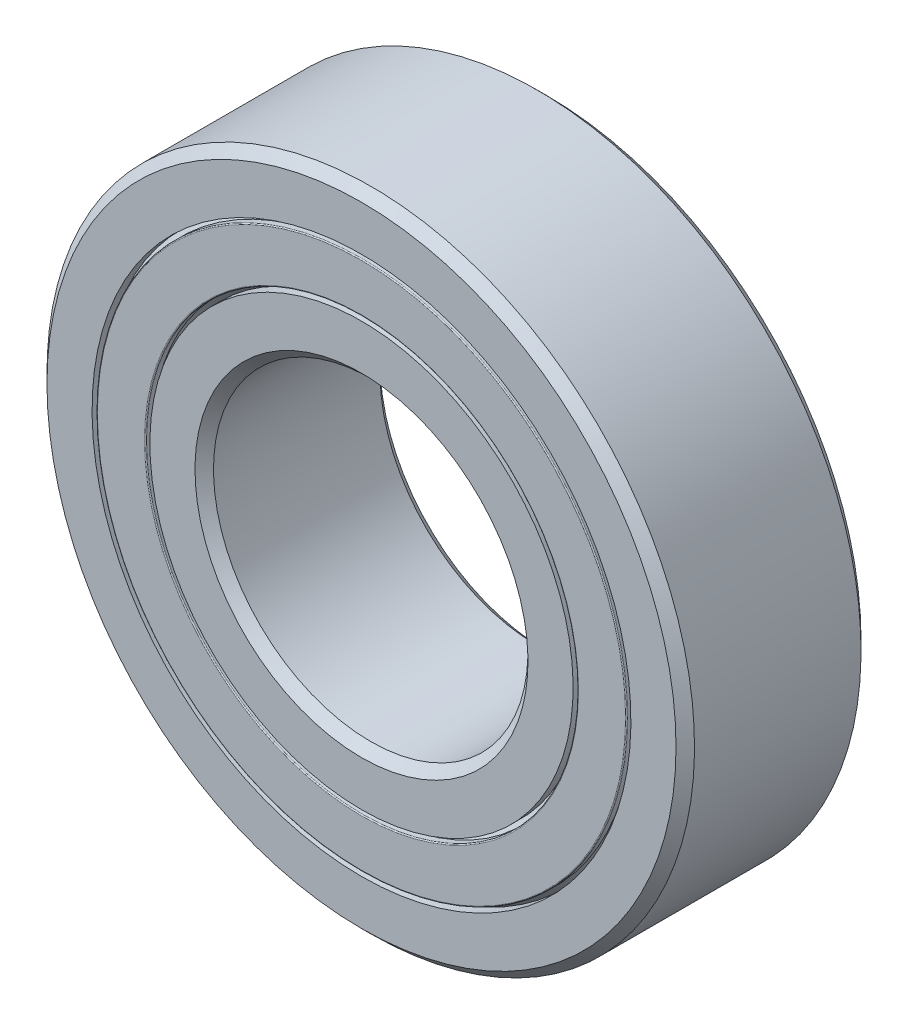
SolidWorks part; units mm, degrees
ref_plane "Front Plane" through (0, 0, 0) normal (0, 0, 1) x (1, 0, 0)
ref_plane "Top Plane" through (0, 0, 0) normal (0, 1, 0) x (1, 0, 0)
ref_plane "Right Plane" through (0, 0, 0) normal (1, 0, 0) x (0, 0, -1)
sketch "Sketch1" plane through (0, 0, 0) normal (0, 0, 1) x (1, 0, 0)
  line L0 (-17.5, 0) -> (17.5, 0) construction
  line L1 (-8.5, 0) -> (8.5, 0) construction
  circle A0 centre (0, 0) radius 8.5 construction
  circle A1 centre (0, 0) radius 17.5 construction
  point P3 (0, 0)
  point P6 (0, 0)
  point P7 (0, -8.5)
  point P11 (0, -17.5)
  point P12 (0, 8.5)
  point P13 (0, 17.5)
  dimension "OD" = 35
  dimension "ID" = 17
sketch "Sketch2" plane through (0, 0, 0) normal (1, 0, 0) x (0, 0, -1)
  line L0 (-5, 17.5) -> (5, 17.5) construction
  line L1 (0, 17.5) -> (0, -17.5) construction
  line L2 (4.5, 17.5) -> (-4.5, 17.5)
  line L3 (-4.5, 17.5) -> (-5, 17)
  line L4 (-5, 17) -> (-5, 14.5625)
  line L5 (-5, 14.5625) -> (-2.2222, 14.5625)
  line L6 (5, 14.5625) -> (2.2222, 14.5625)
  line L7 (5, 17) -> (5, 14.5625)
  line L8 (4.5, 17.5) -> (5, 17)
  line L9 (0, 17.5) -> (0, 13) construction
  line L10 (0, 13) -> (0, 8.5) construction
  line L11 (0, 17.5) -> (0, -17.5) construction
  line L12 (-5, 0) -> (5, 0) construction
  line L13 (5, 8.5) -> (-5, 8.5) construction
  line L14 (0, 15.7166) -> (0, 10.2834) construction
  line L15 (-5, -8.5) -> (5, -8.5) construction
  line L16 (-5, 8.5) -> (-5, -8.5) construction
  line L17 (5, 17.5) -> (5, -17.5) construction
  line L18 (-5, 14.5625) -> (-5, 14.4063) construction
  line L19 (-5, 14.4063) -> (-5, 14.25) construction
  line L20 (-5, 14.25) -> (-5, 14.0938) construction
  line L21 (-5, 14.0938) -> (-5, 13.9375) construction
  line L22 (-5, 13.9375) -> (-5, 13.7813) construction
  line L24 (-3.6111, 14.5625) -> (-3.6111, 13) construction
  arc A0 (-2.2222, 14.5625) -> (2.2222, 14.5625) centre (0, 13) cw
  circle A1 centre (0, 13) radius 2.7166 construction
  point P14 (0, 8.5)
  point P17 (0, 0)
  point P21 (0, 17.5)
  point P29 (0, 8.5)
  point P30 (0, -8.5)
  point P46 (-3.6111, 13.7813)
  dimension "Width" = 10
  dimension "D1" = 45
  dimension "D2" = 0.5
  dimension "D3" = 4.4444
  dimension "D4" = 1.5625
  dimension "For Shaft Diameter" = 17
  dimension "For Housing ID" = 35
sketch "Sketch3" plane through (0, 0, 0) normal (1, 0, 0) x (0, 0, -1)
  line L0 (4.5, 17.5) -> (5, 17) construction
  line L1 (5, 17) -> (5, 14.5625) construction
  line L2 (5, 14.5625) -> (2.2222, 14.5625) construction
  line L3 (-5, 14.5625) -> (-2.2222, 14.5625) construction
  line L4 (-5, 17) -> (-5, 14.5625) construction
  line L5 (-4.5, 17.5) -> (-5, 17) construction
  line L6 (4.5, 17.5) -> (-4.5, 17.5) construction
  line L7 (4.5, 17.5) -> (5, 17)
  line L8 (5, 17) -> (5, 14.5625)
  line L9 (5, 14.5625) -> (2.2222, 14.5625)
  line L10 (-5, 14.5625) -> (-2.2222, 14.5625)
  line L11 (-5, 17) -> (-5, 14.5625)
  line L12 (-4.5, 17.5) -> (-5, 17)
  line L13 (4.5, 17.5) -> (-4.5, 17.5)
  arc A0 (2.2222, 14.5625) -> (-2.2222, 14.5625) centre (0, 13) ccw construction
  arc A1 (2.2222, 14.5625) -> (-2.2222, 14.5625) centre (0, 13) ccw
revolve "Revolve1" add sketch "Sketch3" angle 360 about L12
sketch "Sketch4" plane through (0, 0, 0) normal (1, 0, 0) x (0, 0, -1)
  line L0 (0, 17.5) -> (0, -17.5) construction
  line L1 (0, 17.5) -> (0, -17.5) construction
  line L2 (-4.5, 8.5) -> (-5, 9)
  line L3 (-5, 9) -> (-5, 11.4375)
  line L5 (-5, 11.4375) -> (-2.2222, 11.4375)
  line L6 (-4.5, 8.5) -> (4.5, 8.5)
  line L8 (4.5, 8.5) -> (5, 9)
  line L10 (5, 9) -> (5, 11.4375)
  line L11 (5, 11.4375) -> (2.2222, 11.4375)
  line L12 (-5, 17) -> (-5, 14.5625) construction
  line L13 (4.5, 17.5) -> (5, 17) construction
  line L15 (5, -17) -> (5, 17) construction
  line L16 (4.5, 17.5) -> (4.5, -17.5) construction
  arc A1 (2.2222, 11.4375) -> (-2.2222, 11.4375) centre (0, 13) cw
  circle A2 centre (0, 13) radius 2.7166 construction
  point P1 (0, 8.5)
revolve "Revolve2" add sketch "Sketch4" angle 360 about L12
sketch "Sketch5" plane through (0, 0, 0) normal (1, 0, 0) x (0, 0, -1)
  line L0 (-2.7166, 13) -> (2.7166, 13)
  arc A2 (-2.7166, 13) -> (2.7166, 13) centre (0, 13) cw
  arc A3 (2.2222, 14.5625) -> (-2.2222, 14.5625) centre (0, 13) ccw construction
revolve "Revolve3" add sketch "Sketch5" angle 360 about L0
sketch "Sketch6" plane through (0, 0, 0) normal (1, 0, 0) x (0, 0, -1)
  line L0 (-5, 14.5625) -> (-5, 13.7813) construction
  line L1 (-5, 17) -> (-5, -17) construction
  line L2 (-5, 13.7813) -> (-5, 13) construction
  line L3 (-5, 13) -> (-5, 12.2187) construction
  line L4 (-5, 12.2187) -> (-5, 11.4375) construction
  line L5 (-5, 13.7813) -> (-4.6003, 13.7813) construction
  line L7 (-2.6018, 13.7813) -> (-2.6018, 12.2188) construction
  line L8 (-4.6003, 13.7813) -> (-4.2006, 13.7813) construction
  line L10 (0, 17.5) -> (0, -17.5) construction
  line L11 (0, 17.5) -> (0, -17.5) construction
  line L12 (-4.2006, 13.7813) -> (-3.8009, 13.7813) construction
  line L13 (-3.8009, 13.7813) -> (-3.4012, 13.7813) construction
  line L14 (-3.4012, 13.7813) -> (-3.0015, 13.7813) construction
  line L15 (-3.0015, 13.7813) -> (-2.6018, 13.7813) construction
  line L16 (-2.6018, 13.7813) -> (-3.0015, 13.7813)
  line L17 (-3.0015, 12.2188) -> (-3.4012, 12.2188) construction
  line L18 (-3.0015, 12.2188) -> (-2.6018, 12.2188)
  line L19 (-3.4012, 12.2188) -> (-3.4012, 13.7813) construction
  line L20 (-3.2013, 13.7813) -> (-3.2013, 12.2188) construction
  circle A0 centre (0, 13) radius 2.7166 construction
  circle A1 centre (0, 13) radius 2.7166 construction
  arc A2 (-3.0015, 13.7813) -> (-3.0015, 12.2188) centre (-1.5744, 13) ccw
  arc A3 (-2.6018, 13.7813) -> (-2.6018, 12.2188) centre (0, 13) ccw
  point P28 (-3.2013, 13)
revolve "Revolve4" add sketch "Sketch6" angle 360 about L11
pattern_circular "CirPattern1" count 10 over 360 about axis through (0, 0, 0) along (0, 0, 1) of bodies 134 104
sketch "Sketch7" plane through (0, 0, 0) normal (0, 0, 1) x (1, 0, 0)
  line L0 (0, 11.4375) -> (0, 11.9583) construction
  line L1 (0, 10.2834) -> (0, 15.7166) construction
  line L2 (0, 11.9583) -> (0, 12.4792) construction
  line L3 (0, 12.4792) -> (0, 13) construction
  line L4 (0, 13) -> (0, 13.5208) construction
  line L5 (0, 13.5208) -> (0, 14.0417) construction
  line L6 (0, 14.0417) -> (0, 14.5625) construction
  line L7 (0, 17) -> (0, 14.5625) construction
  line L8 (0, 17.5) -> (0, -17.5) construction
  circle A0 centre (0, 0) radius 11.4375 construction
  circle A1 centre (0, 0) radius 13
  circle A2 centre (0, 0) radius 13.7813
  point P19 (0, 13.7813)
extrude "Boss-Extrude1" add sketch "Sketch7" along normal mid plane 1.6667 separate body
sketch "Sketch8" plane through (0, 0, 0) normal (1, 0, 0) x (0, 0, -1)
  line L0 (-5, 14.4063) -> (-5, 14.25) construction
  line L1 (-5, 14.3281) -> (-4.6296, 14.3281)
  line L2 (-5, 14.3281) -> (-5, 11.6719)
  line L3 (-5, 11.6719) -> (-4.6296, 11.6719)
  line L4 (-4.4444, 14.3281) -> (-4.4444, 11.6719)
  line L5 (0, 17.5) -> (0, 13) construction
  line L10 (-4.6296, 14.3281) -> (-4.4444, 14.5625)
  line L11 (-5, 14.5625) -> (-2.2222, 14.5625) construction
  line L12 (-4.4444, 14.5625) -> (-4.4444, 14.3281)
  line L13 (-4.6296, 11.6719) -> (-4.4444, 11.4375)
  line L14 (-4.4444, 11.4375) -> (-4.4444, 11.6719)
  line L15 (-5, 14.5625) -> (-4.8148, 14.5625) construction
  line L16 (5, 14.3281) -> (5, 11.6719)
  line L17 (5, 11.6719) -> (4.6296, 11.6719)
  line L18 (4.6296, 11.6719) -> (4.4444, 11.4375)
  line L19 (4.4444, 11.4375) -> (4.4444, 11.6719)
  line L20 (4.4444, 14.3281) -> (4.4444, 11.6719)
  line L21 (4.4444, 14.5625) -> (4.4444, 14.3281)
  line L22 (4.6296, 14.3281) -> (4.4444, 14.5625)
  line L23 (5, 14.3281) -> (4.6296, 14.3281)
  line L24 (-4.8148, 14.5625) -> (-4.6296, 14.5625) construction
  line L25 (-4.6296, 14.5625) -> (-4.4444, 14.5625) construction
  line L27 (-5, 11.4375) -> (-2.2222, 11.4375) construction
  point P23 (-5, 14.3281)
  dimension "D1" = 0.5556
revolve "Revolve5" add sketch "Sketch8" angle 360 about L12
fillet "Fillet1" radius 0.0556 2 edges at (0, -14.3281, 5) (0, -11.6719, 5)
fillet "Fillet2" radius 0.0556 2 edges at (0, -11.6719, -5) (0, -14.3281, -5)
equation "\"D2@Sketch2\" = \"Width@Sketch2\" * .05"
equation "\"D3@Sketch2\" = \"Width@Sketch2\" / 2.25"
equation "\"D4@Sketch2\"=( \"OD@Sketch1\" - \"Width@Sketch2\" )  *.5*.125"
equation "\"D1@Boss-Extrude1\" = \"Width@Sketch2\" / 6"
equation "\"D1@Sketch8\"=(\"Width@Sketch2\"-\"D3@Sketch2\")*.5*.2"
equation "\"D1@Fillet1\"=\"d1@sketch8\"*.1"
equation "\"D1@Fillet2\"=\"d1@fillet1\""
